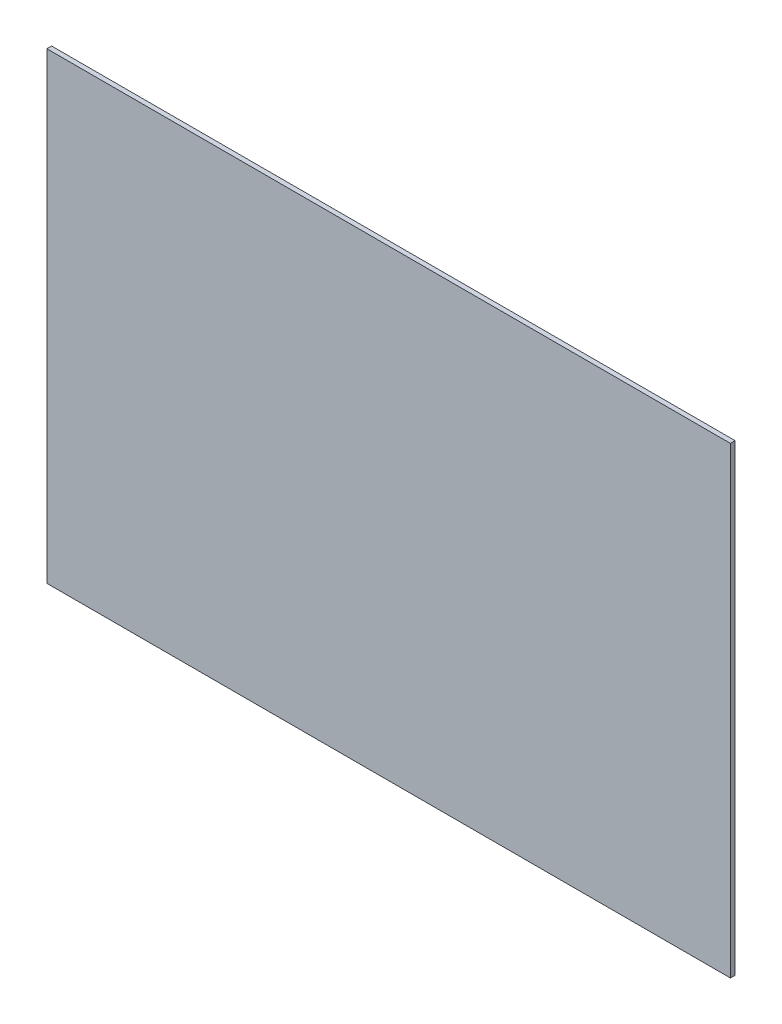
SolidWorks part; units mm, degrees
material "5052-H32"
ref_plane "X-Y Datum" through (0, 0, 0) normal (0, 0, 1) x (1, 0, 0)
ref_plane "X-Z Datum" through (0, 0, 0) normal (0, 1, 0) x (1, 0, 0)
ref_plane "Y-Z Datum" through (0, 0, 0) normal (1, 0, 0) x (0, 0, -1)
sketch "Sketch1" plane through (0, 0, 0) normal (0, 0, 1) x (1, 0, 0)
  line L1 (-229.745, 155.63) -> (229.745, 155.63)
  line L2 (-229.745, 155.63) -> (-229.745, -155.63)
  line L3 (-229.745, -155.63) -> (229.745, -155.63)
  line L4 (229.745, 155.63) -> (229.745, -155.63)
  line L5 (-229.745, 155.63) -> (229.745, -155.63) construction
  line L6 (-229.745, -155.63) -> (229.745, 155.63) construction
  point P0 (0, 0)
  dimension "D1" = 459.49
  dimension "D2" = 311.26
extrude "Boss-Extrude1" add sketch "Sketch1" along normal blind 3.175
